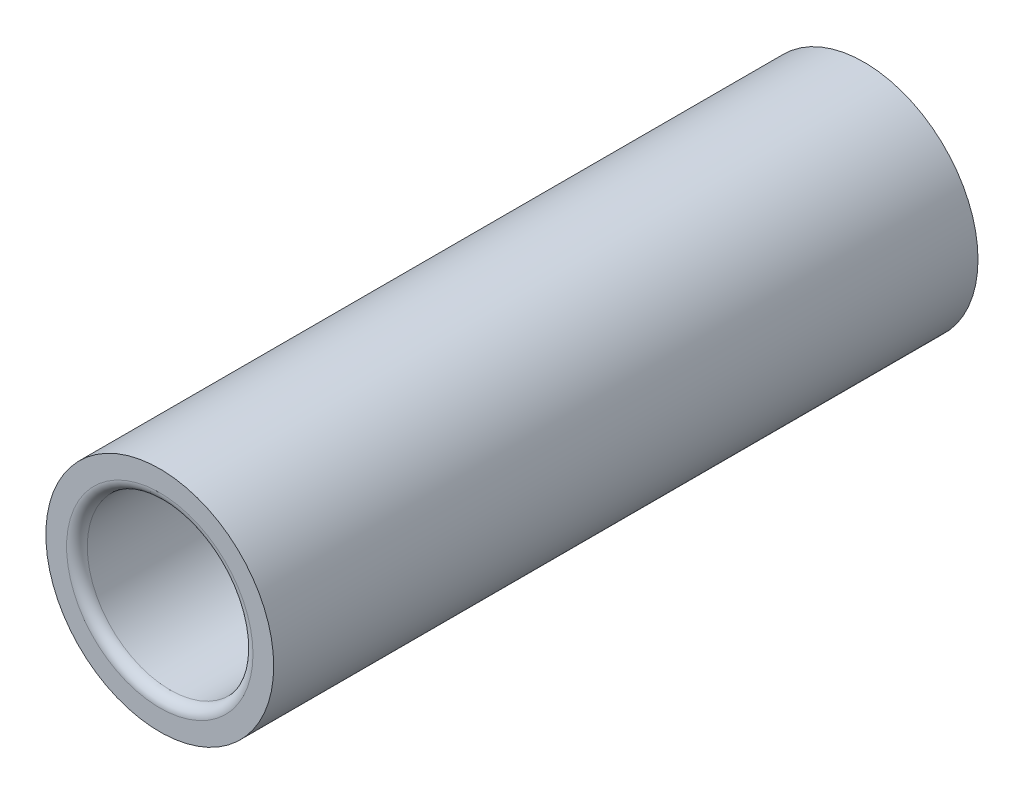
SolidWorks part; units mm, degrees
ref_plane "Front Plane" through (0, 0, 0) normal (0, 0, 1) x (1, 0, 0)
ref_plane "Top Plane" through (0, 0, 0) normal (0, 1, 0) x (1, 0, 0)
ref_plane "Right Plane" through (0, 0, 0) normal (1, 0, 0) x (0, 0, -1)
sketch "Sketch1" plane through (0, 0, 0) normal (0, 0, 1) x (1, 0, 0)
  circle A0 centre (0, 0) radius 11
  circle A1 centre (0, 0) radius 8
  dimension "D1" = 16
  dimension "D2" = 22
extrude "Boss-Extrude1" add sketch "Sketch1" along normal mid plane 68
fillet "Fillet1" radius 1 2 edges at (8, 0, -34) (8, 0, 34)
